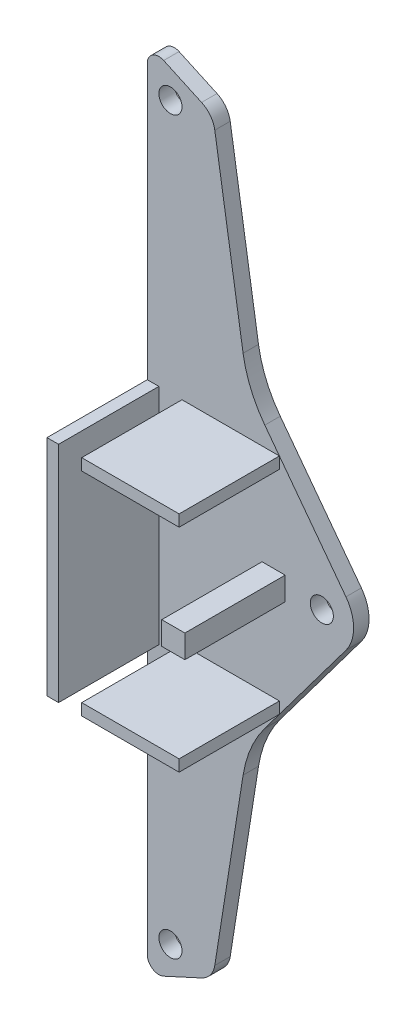
SolidWorks part; units mm, degrees
ref_plane "Ön Düzlem" through (0, 0, 0) normal (0, 0, 1) x (1, 0, 0)
ref_plane "Üst Düzlem" through (0, 0, 0) normal (0, 1, 0) x (1, 0, 0)
ref_plane "Sağ Düzlem" through (0, 0, 0) normal (1, 0, 0) x (0, 0, -1)
sketch "Sketch1" plane through (0, 0, 0) normal (0, 0, 1) x (1, 0, 0)
  line L0 (0, 52.3762) -> (0, -52.3762)
  line L1 (0, -52.3762) -> (8.5, -48.4762)
  line L2 (8.5, -48.4762) -> (13, -20)
  line L3 (13, -20) -> (28, 0)
  line L4 (0, 0) -> (28, 0) construction
  line L5 (13, 20) -> (28, 0)
  line L6 (8.5, 48.4762) -> (13, 20)
  line L7 (0, 52.3762) -> (8.5, 48.4762)
  circle A0 centre (3, -47.3762) radius 1.5
  circle A1 centre (22.6238, 0) radius 1.5
  circle A2 centre (3, 47.3762) radius 1.5
  dimension "D1" = 3
  dimension "D2" = 94.7523
  dimension "D3" = 5
  dimension "D4" = 8.5
  dimension "D5" = 3.9
  dimension "D6" = 20
  dimension "D7" = 19.6238
  dimension "D8" = 3
  dimension "D9" = 28
  dimension "D10" = 13
extrude "Boss-Extrude1" add sketch "Sketch1" along normal blind 2
fillet "Fillet1" radius 15 2 edges at (13, -20, 1) (13, 20, 1)
fillet "Fillet2" radius 3 2 edges at (8.5, 48.4762, 1) (8.5, -48.4762, 1)
fillet "Fillet3" radius 1.5 2 edges at (0, -52.3762, 1) (0, 52.3762, 1)
fillet "Fillet4" radius 5 1 edges at (28, 0, 1)
sketch "Sketch2" plane through (0, 0, 2) normal (0, 0, 1) x (1, 0, 0)
  line L0 (15.2348, -17.0203) -> (25.75, -3) construction
  line L1 (17.125, 14.5) -> (0, 14.5)
  line L2 (17.125, 14.5) -> (17.125, -14.5)
  line L3 (17.125, -14.5) -> (0, -14.5)
  line L4 (0, 14.5) -> (0, -14.5)
  line L5 (17.125, 14.5) -> (0, -14.5) construction
  line L6 (17.125, -14.5) -> (0, 14.5) construction
  line L7 (0, 50.0376) -> (0, -50.0376) construction
  line L10 (15.625, 13) -> (1.5, 13)
  line L11 (1.5, 13) -> (1.5, -13)
  line L12 (15.625, -13) -> (1.5, -13)
  line L13 (15.625, 13) -> (15.625, -13)
  line L14 (15.625, -13) -> (17.125, -13)
  line L15 (15.625, 13) -> (17.125, 13)
  line L16 (15.625, 0) -> (17.125, 0) construction
  line L18 (17.875, 1.5) -> (14.875, 1.5)
  line L19 (17.875, 1.5) -> (17.875, -1.5)
  line L20 (17.875, -1.5) -> (14.875, -1.5)
  line L21 (14.875, 1.5) -> (14.875, -1.5)
  line L22 (17.875, 1.5) -> (14.875, -1.5) construction
  line L23 (17.875, -1.5) -> (14.875, 1.5) construction
  point P0 (8.5625, 0)
  point P18 (16.375, 0)
  line M10 (0, 50.0376) -> (0, -50.0376)
  dimension "D1" = 29
  dimension "D3" = 3
  dimension "D2" = 1.5
extrude "Boss-Extrude2" add sketch "Sketch2" along normal blind 13 contours L10 L15 L2 L1 L3 L14 L12 L11 M10 | L20 L2 L18 L13 | L20 L19 L18 L2 | L18 L21 L20 L13
sketch "Sketch4" plane through (0, 0, 15) normal (0, 0, 1) x (1, 0, 0)
  line L0 (1.5, 13) -> (1.5, -13) construction
  line L1 (4.5, 14.5) -> (1.5, 14.5)
  line L2 (4.5, 14.5) -> (4.5, -14.5)
  line L3 (4.5, -14.5) -> (1.5, -14.5)
  line L4 (1.5, 14.5) -> (1.5, -14.5)
  line L5 (4.5, 14.5) -> (1.5, -14.5) construction
  line L6 (4.5, -14.5) -> (1.5, 14.5) construction
  line L7 (17.125, 14.5) -> (0, 14.5) construction
  point P0 (3, 0)
  dimension "D1" = 3
extrude "Cut-Extrude1" cut sketch "Sketch4" against normal up to surface (13 mm away) up to face at (8.845, 35.6956, 2)
